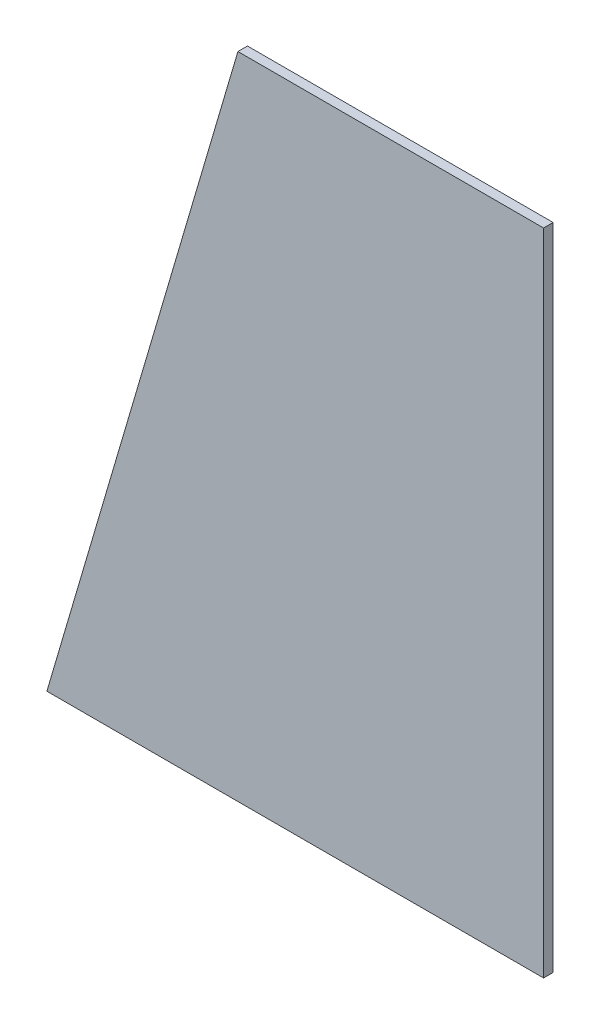
SolidWorks part; units mm, degrees
material "PVC 0.007 Plasticized"
ref_plane "Front Plane" through (0, 0, 0) normal (0, 0, 1) x (1, 0, 0)
ref_plane "Top Plane" through (0, 0, 0) normal (0, 1, 0) x (1, 0, 0)
ref_plane "Right Plane" through (0, 0, 0) normal (1, 0, 0) x (0, 0, -1)
sketch "Sketch1" plane through (0, 0, 0) normal (0, 0, 1) x (1, 0, 0)
  line L5 (-101.6, 107.95) -> (0, 107.95)
  line L6 (-165.1, -107.95) -> (0, -107.95)
  line L10 (0, 107.95) -> (0, -107.95)
  line L12 (-101.6, 107.95) -> (-165.1, -107.95)
  point P0 (0, 0)
  dimension "D1" = 101.6
  dimension "D2" = 165.1
  dimension "D3" = 215.9
extrude "Boss-Extrude1" add sketch "Sketch1" against normal blind 3.175
